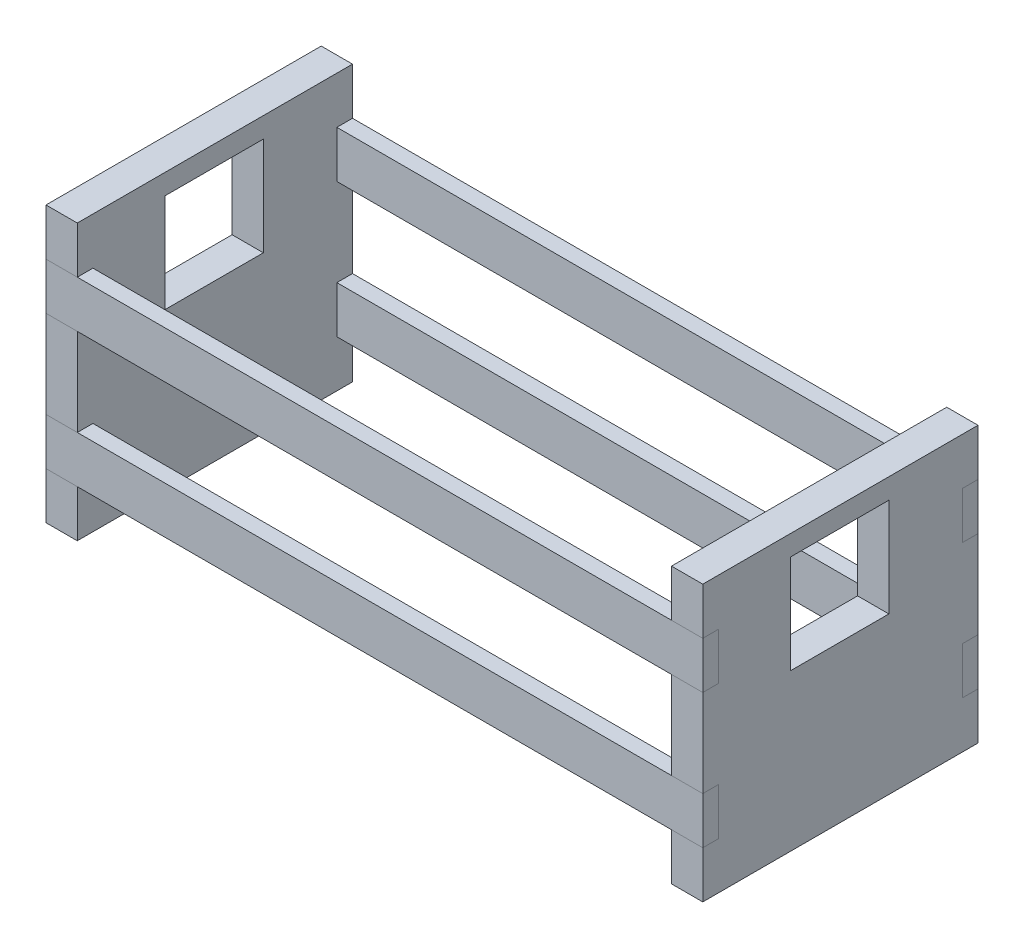
SolidWorks part; units mm, degrees
ref_plane "Front Plane" through (0, 0, 0) normal (0, 0, 1) x (1, 0, 0)
ref_plane "Top Plane" through (0, 0, 0) normal (0, 1, 0) x (1, 0, 0)
ref_plane "Right Plane" through (0, 0, 0) normal (1, 0, 0) x (0, 0, -1)
sketch "Sketch1" plane through (0, 0, 0) normal (1, 0, 0) x (0, 0, -1)
  line L1 (0, 0) -> (22.352, 0)
  line L2 (0, 0) -> (0, 22.352)
  line L3 (0, 22.352) -> (22.352, 22.352)
  line L4 (22.352, 0) -> (22.352, 22.352)
  dimension "D1" = 22.352
  dimension "D2" = 22.352
extrude "Boss-Extrude1" add sketch "Sketch1" along normal blind 2.54
pattern_linear "LPattern1" count 2 spacing 50.8 along (-1, 0, 0) of bodies 101
sketch "Sketch2" plane through (2.54, 0, 0) normal (1, 0, 0) x (0, 0, -1)
  line L0 (0, 0) -> (22.352, 0) construction
  line L1 (7.112, 20.701) -> (15.113, 20.701)
  line L2 (7.112, 20.701) -> (7.112, 12.7)
  line L3 (7.112, 12.7) -> (15.113, 12.7)
  line L4 (15.113, 20.701) -> (15.113, 12.7)
  line L5 (0, 22.352) -> (0, 0) construction
  line L9 (11.176, 22.352) -> (11.176, 0) construction
  line L14 (22.352, 22.352) -> (0, 22.352) construction
  line L15 (0, 11.176) -> (22.352, 11.176) construction
  line L29 (0, 18.542) -> (1.27, 18.542)
  line L30 (0, 18.542) -> (0, 14.732)
  line L31 (0, 14.732) -> (1.27, 14.732)
  line L32 (1.27, 18.542) -> (1.27, 14.732)
  line L33 (22.352, 0) -> (22.352, 22.352) construction
  line L34 (22.352, 14.732) -> (21.082, 14.732)
  line L35 (21.082, 18.542) -> (21.082, 14.732)
  line L36 (22.352, 18.542) -> (21.082, 18.542)
  line L37 (22.352, 18.542) -> (22.352, 14.732)
  line L38 (22.352, 3.81) -> (22.352, 7.62)
  line L39 (22.352, 3.81) -> (21.082, 3.81)
  line L40 (21.082, 3.81) -> (21.082, 7.62)
  line L41 (22.352, 7.62) -> (21.082, 7.62)
  line L42 (0, 7.62) -> (1.27, 7.62)
  line L43 (1.27, 3.81) -> (1.27, 7.62)
  line L44 (0, 3.81) -> (1.27, 3.81)
  line L45 (0, 3.81) -> (0, 7.62)
  dimension "D1" = 12.7
  dimension "D2" = 8.001
  dimension "D3" = 7.112
  dimension "D4" = 8.001
  dimension "D5" = 3.81
  dimension "D6" = 1.27
  dimension "D7" = 7.62
extrude "Cut-Extrude1" cut sketch "Sketch2" against normal through all
sketch "Sketch3" plane through (2.54, 0, 0) normal (1, 0, 0) x (0, 0, -1)
  line L1 (0, 18.542) -> (1.27, 18.542)
  line L2 (0, 18.542) -> (0, 14.732)
  line L3 (0, 14.732) -> (1.27, 14.732)
  line L4 (1.27, 18.542) -> (1.27, 14.732)
  line L5 (21.082, 18.542) -> (22.352, 18.542)
  line L6 (21.082, 18.542) -> (21.082, 14.732)
  line L7 (21.082, 14.732) -> (22.352, 14.732)
  line L8 (22.352, 18.542) -> (22.352, 14.732)
  line L9 (21.082, 7.62) -> (22.352, 7.62)
  line L10 (21.082, 7.62) -> (21.082, 3.81)
  line L11 (21.082, 3.81) -> (22.352, 3.81)
  line L12 (22.352, 7.62) -> (22.352, 3.81)
  line L13 (0, 7.62) -> (1.27, 7.62)
  line L14 (0, 7.62) -> (0, 3.81)
  line L15 (0, 3.81) -> (1.27, 3.81)
  line L16 (1.27, 7.62) -> (1.27, 3.81)
  line L17 (1.27, 18.542) -> (0, 18.542)
  line L18 (1.27, 18.542) -> (1.27, 14.732)
  line L19 (1.27, 14.732) -> (0, 14.732)
  line L20 (0, 18.542) -> (0, 14.732)
  line L21 (22.352, 18.542) -> (21.082, 18.542)
  line L22 (22.352, 18.542) -> (22.352, 14.732)
  line L23 (22.352, 14.732) -> (21.082, 14.732)
  line L24 (21.082, 18.542) -> (21.082, 14.732)
  line L25 (22.352, 7.62) -> (21.082, 7.62)
  line L26 (22.352, 7.62) -> (22.352, 3.81)
  line L27 (22.352, 3.81) -> (21.082, 3.81)
  line L28 (21.082, 7.62) -> (21.082, 3.81)
  line L29 (1.27, 7.62) -> (0, 7.62)
  line L30 (1.27, 7.62) -> (1.27, 3.81)
  line L31 (1.27, 3.81) -> (0, 3.81)
  line L32 (0, 7.62) -> (0, 3.81)
  line M6 (0, 18.542) -> (1.27, 18.542)
  line M7 (1.27, 18.542) -> (1.27, 14.732)
  line M8 (1.27, 14.732) -> (0, 14.732)
  line M10 (0, 7.62) -> (1.27, 7.62)
  line M11 (1.27, 7.62) -> (1.27, 3.81)
  line M12 (1.27, 3.81) -> (0, 3.81)
  line M16 (22.352, 3.81) -> (21.082, 3.81)
  line M17 (21.082, 3.81) -> (21.082, 7.62)
  line M18 (21.082, 7.62) -> (22.352, 7.62)
  line M20 (22.352, 14.732) -> (21.082, 14.732)
  line M21 (21.082, 14.732) -> (21.082, 18.542)
  line M22 (21.082, 18.542) -> (22.352, 18.542)
extrude "Boss-Extrude2" add sketch "Sketch3" against normal up to surface (53.34 mm away) separate body contours L2 M6 M8 M7 | L14 M10 M12 M11 | L8 M22 M21 M20 | L12 M18 M17 M16 up to face at (-50.8, 16.7005, -11.1125)
sketch "Sketch5" plane through (2.54, 0, 0) normal (1, 0, 0) x (0, 0, -1)
  line L0 (7.112, 12.7) -> (15.113, 12.7) construction
  line L1 (6.308, 14.732) -> (2.5432, 14.732)
  line L2 (6.308, 14.732) -> (6.308, 17.0327)
  line L3 (6.308, 17.0327) -> (2.5432, 17.0327)
  line L4 (2.5432, 14.732) -> (2.5432, 17.0327)
  dimension "D1" = 2.032
